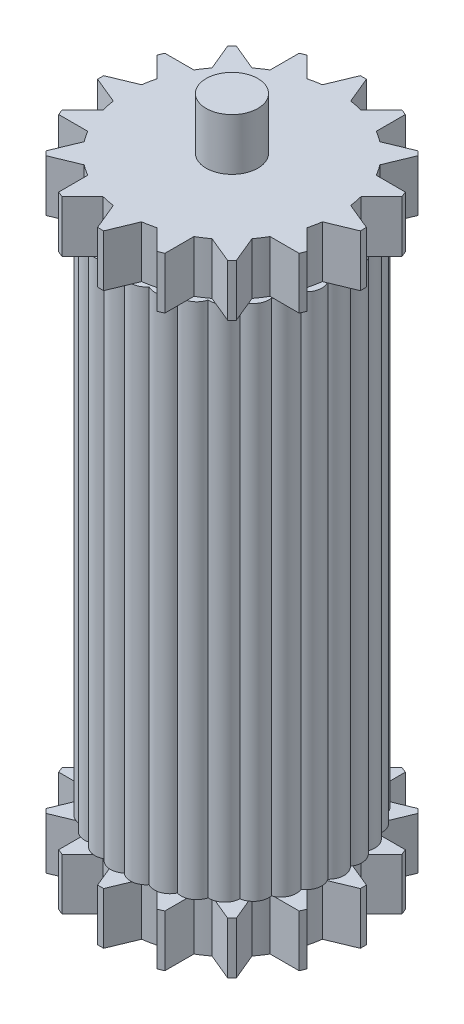
SolidWorks part; units mm, degrees
ref_plane "Front Plane" through (0, 0, 0) normal (1, 0, 0) x (0, 1, 0)
ref_plane "Top Plane" through (0, 0, 0) normal (0, 0, 1) x (0, 1, 0)
ref_plane "Right Plane" through (0, 0, 0) normal (0, 1, 0) x (-1, 0, 0)
sketch "Sketch2" plane through (0, 0, 0) normal (0, 1, 0) x (-1, 0, 0)
  arc A129 (20.6915, 2.1748) -> (20.6915, -2.1748) centre (18.625, 0) cw
  arc A130 (20.6915, -2.1748) -> (19.7872, -6.4292) centre (18.218, -3.8724) cw
  arc A131 (19.7872, -6.4292) -> (18.0181, -10.4027) centre (17.0148, -7.5755) cw
  arc A132 (18.0181, -10.4027) -> (15.4615, -13.9216) centre (15.0679, -10.9475) cw
  arc A133 (15.4615, -13.9216) -> (12.2291, -16.832) centre (12.4626, -13.8411) cw
  arc A134 (12.2291, -16.832) -> (8.4623, -19.0067) centre (9.3125, -16.1297) cw
  arc A135 (8.4623, -19.0067) -> (4.3257, -20.3508) centre (5.7554, -17.7134) cw
  arc A136 (4.3257, -20.3508) -> (0, -20.8055) centre (1.9468, -18.523) cw
  arc A137 (0, -20.8055) -> (-4.3257, -20.3508) centre (-1.9468, -18.523) cw
  arc A138 (-4.3257, -20.3508) -> (-8.4623, -19.0067) centre (-5.7554, -17.7134) cw
  arc A139 (-8.4623, -19.0067) -> (-12.2291, -16.832) centre (-9.3125, -16.1297) cw
  arc A140 (-12.2291, -16.832) -> (-15.4615, -13.9216) centre (-12.4626, -13.8411) cw
  arc A141 (-15.4615, -13.9216) -> (-18.0181, -10.4027) centre (-15.0679, -10.9475) cw
  arc A142 (-18.0181, -10.4027) -> (-19.7872, -6.4292) centre (-17.0148, -7.5755) cw
  arc A143 (-19.7872, -6.4292) -> (-20.6915, -2.1748) centre (-18.218, -3.8724) cw
  arc A144 (-20.6915, -2.1748) -> (-20.6915, 2.1748) centre (-18.625, 0) cw
  arc A145 (-20.6915, 2.1748) -> (-19.7872, 6.4292) centre (-18.218, 3.8724) cw
  arc A146 (-19.7872, 6.4292) -> (-18.0181, 10.4027) centre (-17.0148, 7.5755) cw
  arc A147 (-18.0181, 10.4027) -> (-15.4615, 13.9216) centre (-15.0679, 10.9475) cw
  arc A148 (-15.4615, 13.9216) -> (-12.2291, 16.832) centre (-12.4626, 13.8411) cw
  arc A149 (-12.2291, 16.832) -> (-8.4623, 19.0067) centre (-9.3125, 16.1297) cw
  arc A150 (-8.4623, 19.0067) -> (-4.3257, 20.3508) centre (-5.7554, 17.7134) cw
  arc A151 (-4.3257, 20.3508) -> (0, 20.8055) centre (-1.9468, 18.523) cw
  arc A152 (0, 20.8055) -> (4.3257, 20.3508) centre (1.9468, 18.523) cw
  arc A153 (4.3257, 20.3508) -> (8.4623, 19.0067) centre (5.7554, 17.7134) cw
  arc A154 (8.4623, 19.0067) -> (12.2291, 16.832) centre (9.3125, 16.1297) cw
  arc A155 (12.2291, 16.832) -> (15.4615, 13.9216) centre (12.4626, 13.8411) cw
  arc A156 (15.4615, 13.9216) -> (18.0181, 10.4027) centre (15.0679, 10.9475) cw
  arc A157 (18.0181, 10.4027) -> (19.7872, 6.4292) centre (17.0148, 7.5755) cw
  arc A158 (19.7872, 6.4292) -> (20.6915, 2.1748) centre (18.218, 3.8724) cw
  point P113 (0, 0)
  point P204 (0, 0)
  dimension "D6" = 30
  dimension "D5" = 3
extrude "Boss-Extrude2" add sketch "Sketch2" along normal blind 100
sketch "Sketch3" plane through (0, 0, 0) normal (0, -1, 0) x (1, 0, 0)
  line L0 (0, -57.0817) -> (0, 57.0817) construction
  line L1 (0, 25.375) -> (2.1167, 20.2647) construction
  line L2 (0, 25.375) -> (-2.1167, 20.2647) construction
  line L5 (-2.733, 20.1909) -> (2.733, 20.1909) construction
  line L32 (-2.733, 20.1909) -> (-0.5885, 25.3682)
  line L33 (2.733, 20.1909) -> (0.5885, 25.3682)
  line L34 (5.2017, 19.6998) -> (9.1643, 23.6623)
  line L35 (10.2517, 17.6081) -> (10.2517, 23.2119)
  line L36 (12.3446, 16.2096) -> (17.5219, 18.3541)
  line L37 (16.2096, 12.3446) -> (18.3541, 17.5219)
  line L38 (17.6081, 10.2517) -> (23.2119, 10.2517)
  line L39 (19.6998, 5.2017) -> (23.6623, 9.1643)
  line L40 (20.1909, 2.733) -> (25.3682, 0.5885)
  line L41 (20.1909, -2.733) -> (25.3682, -0.5885)
  line L42 (19.6998, -5.2017) -> (23.6623, -9.1643)
  line L43 (17.6081, -10.2517) -> (23.2119, -10.2517)
  line L44 (16.2096, -12.3446) -> (18.3541, -17.5219)
  line L45 (12.3446, -16.2096) -> (17.5219, -18.3541)
  line L46 (10.2517, -17.6081) -> (10.2517, -23.2119)
  line L47 (5.2017, -19.6998) -> (9.1643, -23.6623)
  line L48 (2.733, -20.1909) -> (0.5885, -25.3682)
  line L49 (-2.733, -20.1909) -> (-0.5885, -25.3682)
  line L50 (-5.2017, -19.6998) -> (-9.1643, -23.6623)
  line L51 (-10.2517, -17.6081) -> (-10.2517, -23.2119)
  line L52 (-12.3446, -16.2096) -> (-17.5219, -18.3541)
  line L53 (-16.2096, -12.3446) -> (-18.3541, -17.5219)
  line L54 (-17.6081, -10.2517) -> (-23.2119, -10.2517)
  line L55 (-19.6998, -5.2017) -> (-23.6623, -9.1643)
  line L56 (-20.1909, -2.733) -> (-25.3682, -0.5885)
  line L57 (-20.1909, 2.733) -> (-25.3682, 0.5885)
  line L58 (-19.6998, 5.2017) -> (-23.6623, 9.1643)
  line L59 (-17.6081, 10.2517) -> (-23.2119, 10.2517)
  line L60 (-16.2096, 12.3446) -> (-18.3541, 17.5219)
  line L61 (-12.3446, 16.2096) -> (-17.5219, 18.3541)
  line L62 (-10.2517, 17.6081) -> (-10.2517, 23.2119)
  line L63 (-5.2017, 19.6998) -> (-9.1643, 23.6623)
  arc A28 (-16.2096, 12.3446) -> (-17.6081, 10.2517) centre (0, 0) ccw
  arc A29 (-23.2119, 10.2517) -> (-23.6623, 9.1643) centre (0, 0) ccw
  arc A30 (-17.5219, 18.3541) -> (-18.3541, 17.5219) centre (0, 0) ccw
  arc A31 (-10.2517, 17.6081) -> (-12.3446, 16.2096) centre (0, 0) ccw
  arc A32 (-9.1643, 23.6623) -> (-10.2517, 23.2119) centre (0, 0) ccw
  arc A33 (0.5885, 25.3682) -> (-0.5885, 25.3682) centre (0, 0) ccw
  arc A34 (10.2517, 23.2119) -> (9.1643, 23.6623) centre (0, 0) ccw
  arc A35 (-2.733, 20.1909) -> (-5.2017, 19.6998) centre (0, 0) ccw
  arc A36 (5.2017, 19.6998) -> (2.733, 20.1909) centre (0, 0) ccw
  arc A37 (18.3541, 17.5219) -> (17.5219, 18.3541) centre (0, 0) ccw
  arc A38 (12.3446, 16.2096) -> (10.2517, 17.6081) centre (0, 0) ccw
  arc A39 (17.6081, 10.2517) -> (16.2096, 12.3446) centre (0, 0) ccw
  arc A40 (23.6623, 9.1643) -> (23.2119, 10.2517) centre (0, 0) ccw
  arc A41 (25.3682, -0.5885) -> (25.3682, 0.5885) centre (0, 0) ccw
  arc A42 (23.2119, -10.2517) -> (23.6623, -9.1643) centre (0, 0) ccw
  arc A43 (20.1909, 2.733) -> (19.6998, 5.2017) centre (0, 0) ccw
  arc A44 (19.6998, -5.2017) -> (20.1909, -2.733) centre (0, 0) ccw
  arc A45 (17.5219, -18.3541) -> (18.3541, -17.5219) centre (0, 0) ccw
  arc A46 (9.1643, -23.6623) -> (10.2517, -23.2119) centre (0, 0) ccw
  arc A47 (10.2517, -17.6081) -> (12.3446, -16.2096) centre (0, 0) ccw
  arc A48 (16.2096, -12.3446) -> (17.6081, -10.2517) centre (0, 0) ccw
  arc A49 (-0.5885, -25.3682) -> (0.5885, -25.3682) centre (0, 0) ccw
  arc A50 (-10.2517, -23.2119) -> (-9.1643, -23.6623) centre (0, 0) ccw
  arc A51 (-5.2017, -19.6998) -> (-2.733, -20.1909) centre (0, 0) ccw
  arc A52 (2.733, -20.1909) -> (5.2017, -19.6998) centre (0, 0) ccw
  arc A53 (-18.3541, -17.5219) -> (-17.5219, -18.3541) centre (0, 0) ccw
  arc A54 (-23.6623, -9.1643) -> (-23.2119, -10.2517) centre (0, 0) ccw
  arc A55 (-12.3446, -16.2096) -> (-10.2517, -17.6081) centre (0, 0) ccw
  arc A56 (-17.6081, -10.2517) -> (-16.2096, -12.3446) centre (0, 0) ccw
  arc A57 (-20.1909, -2.733) -> (-19.6998, -5.2017) centre (0, 0) ccw
  arc A58 (-25.3682, 0.5885) -> (-25.3682, -0.5885) centre (0, 0) ccw
  arc A59 (-19.6998, 5.2017) -> (-20.1909, 2.733) centre (0, 0) ccw
  point P13 (0, 57.0817)
  point P17 (0, 47.4976)
  point P78 (0, 0)
  dimension "D2" = 50.75
  dimension "D1" = 40.75
  dimension "D3" = 22.5
  dimension "D4" = 22.5
  dimension "D5" = 5.466
  dimension "D6" = 16
extrude "Boss-Extrude3" add sketch "Sketch3" along normal blind 10
ref_plane "Plane1" through (0, 50, 0) normal (0, -1, 0) x (-1, 0, 0)
mirror "Mirror1" about plane through (0, 50, 0) normal (0, -1, 0) of "Boss-Extrude3"
sketch "Sketch4" plane through (0, -10, 0) normal (0, -1, 0) x (1, 0, 0)
  circle A0 centre (0, 0) radius 5
  dimension "D1" = 10
extrude "Boss-Extrude4" add sketch "Sketch4" along normal blind 10
mirror "Mirror2" about plane through (0, 50, 0) normal (0, -1, 0) of "Boss-Extrude4"
